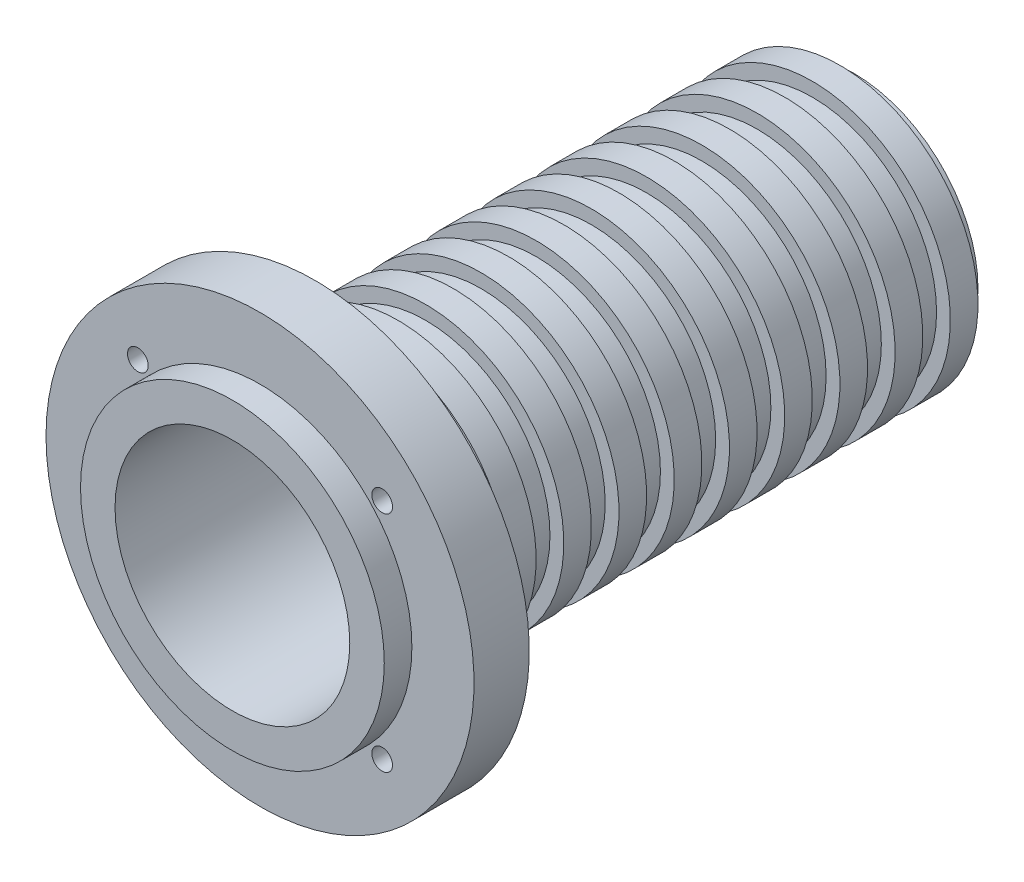
SolidWorks part; units mm, degrees
ref_plane "Front Plane" through (0, 0, 0) normal (0, 0, 1) x (1, 0, 0)
ref_plane "Top Plane" through (0, 0, 0) normal (0, 1, 0) x (1, 0, 0)
ref_plane "Right Plane" through (0, 0, 0) normal (1, 0, 0) x (0, 0, -1)
sketch "Sketch1" plane through (0, 0, 0) normal (0, 0, 1) x (1, 0, 0)
  circle A0 centre (0, 0) radius 29.9458
  circle A1 centre (0, 0) radius 22
  circle A2 centre (0, 0) radius 43.0118
  dimension "D1" = 44
extrude "Boss-Extrude1" add sketch "Sketch1" along normal blind 4 contours A1
sketch "Sketch2" plane through (0, 0, 0) normal (0, 0, -1) x (-1, 0, 0)
  circle A0 centre (0, 0) radius 31
extrude "Boss-Extrude2" add sketch "Sketch2" along normal blind 8
sketch "Sketch3" plane through (0, 0, -8) normal (0, 0, -1) x (-1, 0, 0)
  line L1 (24, 21.9898) -> (-24, 21.9898)
  line L2 (24, 21.9898) -> (24, -21.9898)
  line L3 (24, -21.9898) -> (-24, -21.9898)
  line L4 (-24, 21.9898) -> (-24, -21.9898)
  line L5 (24, 21.9898) -> (-24, -21.9898) construction
  line L6 (24, -21.9898) -> (-24, 21.9898) construction
  circle A0 centre (0, 0) radius 24
  circle A1 centre (-17.6954, 16.2133) radius 1.5
  circle A2 centre (17.6954, 16.2133) radius 1.5
  circle A3 centre (17.6954, -16.2133) radius 1.5
  circle A4 centre (-17.6954, -16.2133) radius 1.5
  dimension "D1" = 48
  dimension "D2" = 3
extrude "Cut-Extrude1" cut sketch "Sketch3" against normal through all contours A0 A1 | A0 A1 | A0 A4 | A0 A4 | A0 A3 | A0 A3 | A0 A2 | A0 A2
sketch "Sketch4" plane through (0, 0, -8) normal (0, 0, -1) x (-1, 0, 0)
  circle A0 centre (0, 0) radius 18
  dimension "D1" = 36
extrude "Boss-Extrude3" add sketch "Sketch4" along normal blind 78
sketch "Sketch5" plane through (0, 0, -86) normal (0, 0, -1) x (-1, 0, 0)
  circle A0 centre (0, 0) radius 17
  dimension "D1" = 34
extrude "Cut-Extrude2" cut sketch "Sketch5" against normal through all
sketch "Sketch6" plane through (0, 0, -8) normal (0, 0, -1) x (-1, 0, 0)
  circle A0 centre (0, 0) radius 20
  circle M1 centre (0, 0) radius 18
  dimension "D1" = 40
extrude "Boss-Extrude4" add sketch "Sketch6" along normal blind 4 contours A0 M1
pattern_linear "LPattern1" count 10 spacing 8 along (0, 0, -1) of "Boss-Extrude4"
